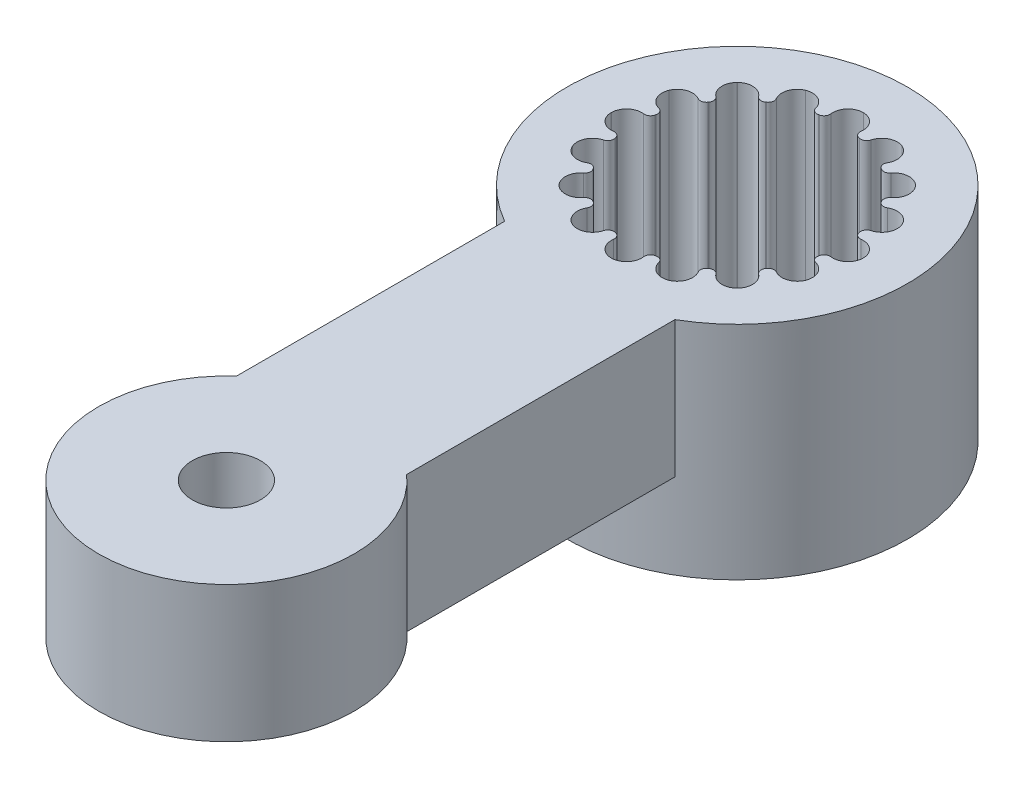
SolidWorks part; units mm, degrees
ref_plane "Ön Düzlem" through (0, 0, 0) normal (0, 0, 1) x (1, 0, 0)
ref_plane "Üst Düzlem" through (0, 0, 0) normal (0, 1, 0) x (1, 0, 0)
ref_plane "Sağ Düzlem" through (0, 0, 0) normal (1, 0, 0) x (0, 0, -1)
sketch "Sketch1" plane through (0, 0, 0) normal (0, 1, 0) x (1, 0, 0)
  circle A0 centre (0, 0) radius 6.1
  circle A1 centre (0, 0) radius 10
  dimension "D1" = 12.2
  dimension "D2" = 20
extrude "Boss-Extrude1" add sketch "Sketch1" along normal blind 8
sketch "Sketch2" plane through (0, 8, 0) normal (0, 1, 0) x (1, 0, 0)
  line L0 (0, 0) -> (0, 7.4) construction
  circle A0 centre (0, 0) radius 7.4 construction
  arc A1 (-0.0006, 7.4) -> (-0.887, 6.3783) centre (0.0047, 6.5) ccw
  circle A2 centre (0, 0) radius 6.1 construction
  arc A3 (0.0006, 7.4) -> (0.887, 6.3783) centre (-0.0047, 6.5) cw
  arc A4 (-0.0006, 7.4) -> (0.0006, 7.4) centre (0, 7.3) cw
  arc A5 (2.8324, 6.8365) -> (3.2603, 5.5533) centre (2.4831, 6.007) cw
  arc A6 (2.8313, 6.8369) -> (1.6214, 6.2322) centre (2.4918, 6.0034) ccw
  arc A7 (2.8313, 6.8369) -> (2.8324, 6.8365) centre (2.7936, 6.7443) cw
  arc A8 (5.233, 5.2322) -> (5.1373, 3.8829) centre (4.5929, 4.5996) cw
  arc A9 (5.2322, 5.233) -> (3.8829, 5.1373) centre (4.5996, 4.5929) ccw
  arc A10 (5.2322, 5.233) -> (5.233, 5.2322) centre (5.1619, 5.1619) cw
  arc A11 (6.8369, 2.8313) -> (6.2322, 1.6214) centre (6.0034, 2.4918) cw
  arc A12 (6.8365, 2.8324) -> (5.5533, 3.2603) centre (6.007, 2.4831) ccw
  arc A13 (6.8365, 2.8324) -> (6.8369, 2.8313) centre (6.7443, 2.7936) cw
  arc A14 (7.4, -0.0006) -> (6.3783, -0.887) centre (6.5, 0.0047) cw
  arc A15 (7.4, 0.0006) -> (6.3783, 0.887) centre (6.5, -0.0047) ccw
  arc A16 (7.4, 0.0006) -> (7.4, -0.0006) centre (7.3, 0) cw
  arc A17 (6.8365, -2.8324) -> (5.5533, -3.2603) centre (6.007, -2.4831) cw
  arc A18 (6.8369, -2.8313) -> (6.2322, -1.6214) centre (6.0034, -2.4918) ccw
  arc A19 (6.8369, -2.8313) -> (6.8365, -2.8324) centre (6.7443, -2.7936) cw
  arc A20 (5.2322, -5.233) -> (3.8829, -5.1373) centre (4.5996, -4.5928) cw
  arc A21 (5.233, -5.2322) -> (5.1373, -3.8829) centre (4.5929, -4.5996) ccw
  arc A22 (5.233, -5.2322) -> (5.2322, -5.233) centre (5.1619, -5.1619) cw
  arc A23 (2.8313, -6.8369) -> (1.6214, -6.2322) centre (2.4918, -6.0034) cw
  arc A24 (2.8324, -6.8365) -> (3.2603, -5.5533) centre (2.4831, -6.007) ccw
  arc A25 (2.8324, -6.8365) -> (2.8313, -6.8369) centre (2.7936, -6.7443) cw
  arc A26 (-0.0006, -7.4) -> (-0.887, -6.3783) centre (0.0048, -6.5) cw
  arc A27 (0.0006, -7.4) -> (0.887, -6.3783) centre (-0.0047, -6.5) ccw
  arc A28 (0.0006, -7.4) -> (-0.0006, -7.4) centre (0, -7.3) cw
  arc A29 (-2.8324, -6.8365) -> (-3.2603, -5.5533) centre (-2.4831, -6.007) cw
  arc A30 (-2.8313, -6.8369) -> (-1.6214, -6.2322) centre (-2.4918, -6.0034) ccw
  arc A31 (-2.8313, -6.8369) -> (-2.8324, -6.8365) centre (-2.7936, -6.7443) cw
  arc A32 (-5.233, -5.2322) -> (-5.1373, -3.8829) centre (-4.5928, -4.5996) cw
  arc A33 (-5.2322, -5.233) -> (-3.8829, -5.1373) centre (-4.5996, -4.5929) ccw
  arc A34 (-5.2322, -5.233) -> (-5.233, -5.2322) centre (-5.1619, -5.1619) cw
  arc A35 (-6.8369, -2.8313) -> (-6.2322, -1.6214) centre (-6.0034, -2.4918) cw
  arc A36 (-6.8365, -2.8324) -> (-5.5533, -3.2603) centre (-6.007, -2.4831) ccw
  arc A37 (-6.8365, -2.8324) -> (-6.8369, -2.8313) centre (-6.7443, -2.7936) cw
  arc A38 (-7.4, 0.0006) -> (-6.3783, 0.887) centre (-6.5, -0.0047) cw
  arc A39 (-7.4, -0.0006) -> (-6.3783, -0.887) centre (-6.5, 0.0047) ccw
  arc A40 (-7.4, -0.0006) -> (-7.4, 0.0006) centre (-7.3, 0) cw
  arc A41 (-6.8365, 2.8324) -> (-5.5533, 3.2603) centre (-6.007, 2.4831) cw
  arc A42 (-6.8369, 2.8313) -> (-6.2322, 1.6214) centre (-6.0034, 2.4918) ccw
  arc A43 (-6.8369, 2.8313) -> (-6.8365, 2.8324) centre (-6.7443, 2.7936) cw
  arc A44 (-5.2322, 5.233) -> (-3.8829, 5.1373) centre (-4.5996, 4.5928) cw
  arc A45 (-5.233, 5.2322) -> (-5.1373, 3.8829) centre (-4.5928, 4.5996) ccw
  arc A46 (-5.233, 5.2322) -> (-5.2322, 5.233) centre (-5.1619, 5.1619) cw
  arc A47 (-2.8313, 6.8369) -> (-1.6214, 6.2322) centre (-2.4918, 6.0034) cw
  arc A48 (-2.8324, 6.8365) -> (-3.2603, 5.5533) centre (-2.4831, 6.007) ccw
  arc A49 (-2.8324, 6.8365) -> (-2.8313, 6.8369) centre (-2.7936, 6.7443) cw
  arc A50 (-1.1668, 5.9874) -> (-1.2133, 5.9781) centre (0, 0) ccw
  arc A51 (-3.3693, 5.0851) -> (-3.4086, 5.0588) centre (0, 0) ccw
  arc A52 (-5.0588, 3.4086) -> (-5.0851, 3.3693) centre (0, 0) ccw
  arc A53 (-5.9781, 1.2133) -> (-5.9874, 1.1668) centre (0, 0) ccw
  arc A54 (-5.9874, -1.1668) -> (-5.9781, -1.2133) centre (0, 0) ccw
  arc A55 (-5.0851, -3.3693) -> (-5.0588, -3.4086) centre (0, 0) ccw
  arc A56 (-3.4086, -5.0588) -> (-3.3693, -5.0851) centre (0, 0) ccw
  arc A57 (-1.2133, -5.9781) -> (-1.1668, -5.9874) centre (0, 0) ccw
  arc A58 (1.1668, -5.9874) -> (1.2133, -5.9781) centre (0, 0) ccw
  arc A59 (3.3693, -5.0851) -> (3.4086, -5.0588) centre (0, 0) ccw
  arc A60 (5.0588, -3.4086) -> (5.0851, -3.3693) centre (0, 0) ccw
  arc A61 (5.9781, -1.2133) -> (5.9874, -1.1668) centre (0, 0) ccw
  arc A62 (5.9874, 1.1668) -> (5.9781, 1.2133) centre (0, 0) ccw
  arc A63 (5.0851, 3.3693) -> (5.0588, 3.4086) centre (0, 0) ccw
  arc A64 (3.4086, 5.0588) -> (3.3693, 5.0851) centre (0, 0) ccw
  arc A65 (1.2133, 5.9781) -> (1.1668, 5.9874) centre (0, 0) ccw
  arc A66 (-1.1668, 5.9874) -> (-0.887, 6.3783) centre (-1.2338, 6.3309) ccw
  arc A67 (-1.2133, 5.9781) -> (-1.6214, 6.2322) centre (-1.2829, 6.3211) cw
  arc A68 (-3.3693, 5.0851) -> (-3.2603, 5.5533) centre (-3.5626, 5.3768) ccw
  arc A69 (-3.4086, 5.0588) -> (-3.8829, 5.1373) centre (-3.6042, 5.349) cw
  arc A70 (-5.0851, 3.3693) -> (-5.5533, 3.2603) centre (-5.3769, 3.5626) cw
  arc A71 (-5.0588, 3.4086) -> (-5.1373, 3.8829) centre (-5.349, 3.6042) ccw
  arc A72 (-5.9781, 1.2133) -> (-6.2322, 1.6214) centre (-6.3211, 1.2829) ccw
  arc A73 (-5.9874, 1.1668) -> (-6.3783, 0.887) centre (-6.3309, 1.2338) cw
  arc A74 (-5.9874, -1.1668) -> (-6.3783, -0.887) centre (-6.3309, -1.2338) ccw
  arc A75 (-6.2322, -1.6214) -> (-5.9781, -1.2133) centre (-6.3211, -1.2829) ccw
  arc A76 (-5.0588, -3.4086) -> (-5.1373, -3.8829) centre (-5.349, -3.6042) cw
  arc A77 (-5.0851, -3.3693) -> (-5.5533, -3.2603) centre (-5.3768, -3.5626) ccw
  arc A78 (-3.4086, -5.0588) -> (-3.8829, -5.1373) centre (-3.6042, -5.349) ccw
  arc A79 (-3.2603, -5.5533) -> (-3.3693, -5.0851) centre (-3.5626, -5.3769) ccw
  arc A80 (-1.2133, -5.9781) -> (-1.6214, -6.2322) centre (-1.2829, -6.3211) ccw
  arc A81 (-0.887, -6.3783) -> (-1.1668, -5.9874) centre (-1.2338, -6.3309) ccw
  arc A82 (1.1668, -5.9874) -> (0.887, -6.3783) centre (1.2338, -6.3309) ccw
  arc A83 (1.2133, -5.9781) -> (1.6214, -6.2322) centre (1.2829, -6.3211) cw
  arc A84 (3.3693, -5.0851) -> (3.2603, -5.5533) centre (3.5626, -5.3768) ccw
  arc A85 (3.4086, -5.0588) -> (3.8829, -5.1373) centre (3.6042, -5.349) cw
  arc A86 (5.0588, -3.4086) -> (5.1373, -3.8829) centre (5.349, -3.6042) ccw
  arc A87 (5.0851, -3.3693) -> (5.5533, -3.2603) centre (5.3769, -3.5626) cw
  arc A88 (5.9781, -1.2133) -> (6.2322, -1.6214) centre (6.3211, -1.2829) ccw
  arc A89 (5.9874, -1.1668) -> (6.3783, -0.887) centre (6.3309, -1.2338) cw
  arc A90 (5.9874, 1.1668) -> (6.3783, 0.887) centre (6.3309, 1.2338) ccw
  arc A91 (5.9781, 1.2133) -> (6.2322, 1.6214) centre (6.3211, 1.2829) cw
  arc A92 (5.0851, 3.3693) -> (5.5533, 3.2603) centre (5.3768, 3.5626) ccw
  arc A93 (5.0588, 3.4086) -> (5.1373, 3.8829) centre (5.349, 3.6042) cw
  arc A94 (3.4086, 5.0588) -> (3.8829, 5.1373) centre (3.6042, 5.349) ccw
  arc A95 (3.3693, 5.0851) -> (3.2603, 5.5533) centre (3.5626, 5.3769) cw
  arc A96 (1.2133, 5.9781) -> (1.6214, 6.2322) centre (1.2829, 6.3211) ccw
  arc A97 (1.1668, 5.9874) -> (0.887, 6.3783) centre (1.2338, 6.3309) cw
  circle A98 centre (0, 0) radius 6.1
  point P15 (-0.775, 6.0506)
  point P121 (0, 0)
  point P132 (-4.8264, 3.7304)
  point P185 (0.775, 6.0506)
  circle M50 centre (0, 0) radius 6.1
  dimension "D1" = 14.8
  dimension "D3" = 0.9
  dimension "D4" = 0.1
  dimension "D6" = 0.35
  dimension "D2" = 1.55
  dimension "D5" = 16
extrude "Cut-Extrude1" cut sketch "Sketch2" against normal blind 8 contours A71 A69 A44 A46 A45 M50 | A68 A67 A47 A49 A48 M50
sketch "Sketch3" plane through (0, 8, 0) normal (0, 1, 0) x (1, 0, 0)
  line L0 (0, 0) -> (0, -30) construction
  line L1 (-5, -8.6603) -> (-5, -24.4098)
  line L2 (5, -8.6603) -> (5, -24.4098)
  arc A0 (-5, -24.4098) -> (5, -24.4098) centre (0, -30) ccw
  circle A1 centre (0, 0) radius 10 construction
  arc A2 (-5, -8.6603) -> (5, -8.6603) centre (0, 0) ccw
  circle A3 centre (0, -30) radius 2
  dimension "D2" = 15
  dimension "D4" = 4
  dimension "D5" = 10
  dimension "D1" = 30
  dimension "D3" = 5
extrude "Boss-Extrude2" add sketch "Sketch3" against normal blind 8
sketch "Sketch4" plane through (0, 0, 0) normal (0, -1, 0) x (1, 0, 0)
  line L1 (2.1073, 33.65) -> (-2.1073, 33.65)
  line L2 (-2.1073, 33.65) -> (-4.2147, 30)
  line L3 (-4.2147, 30) -> (-2.1073, 26.35)
  line L4 (-2.1073, 26.35) -> (2.1073, 26.35)
  line L5 (2.1073, 26.35) -> (4.2147, 30)
  line L6 (4.2147, 30) -> (2.1073, 33.65)
  circle A0 centre (0, 30) radius 3.65 construction
  dimension "D1" = 7.3
extrude "Cut-Extrude2" cut sketch "Sketch4" against normal blind 5
sketch "Çizim2" plane through (0, 0, 0) normal (0, -1, 0) x (1, 0, 0)
  circle A0 centre (0, 0) radius 10
  arc A1 (-5, 8.6603) -> (5, 8.6603) centre (0, 0) ccw construction
extrude "Yükseklik-Ekstrüzyon1" add sketch "Çizim2" along normal blind 5
sketch "Çizim3" plane through (0, 0, 0) normal (0, 1, 0) x (1, 0, 0)
  line L16 (-0.0006, -7.4) -> (0.0006, -7.4)
  line L17 (2.8313, -6.8369) -> (2.8324, -6.8365)
  line L18 (5.2322, -5.233) -> (5.233, -5.2322)
  line L19 (6.8365, -2.8324) -> (6.8369, -2.8313)
  line L20 (7.4, -0.0006) -> (7.4, 0.0006)
  line L21 (6.8369, 2.8313) -> (6.8365, 2.8324)
  line L22 (5.233, 5.2322) -> (5.2322, 5.233)
  line L23 (2.8324, 6.8365) -> (2.8313, 6.8369)
  line L24 (0.0006, 7.4) -> (-0.0006, 7.4)
  line L25 (-2.8313, 6.8369) -> (-2.8324, 6.8365)
  line L26 (-5.2322, 5.233) -> (-5.233, 5.2322)
  line L27 (-6.8365, 2.8324) -> (-6.8369, 2.8313)
  line L28 (-7.4, 0.0006) -> (-7.4, -0.0006)
  line L29 (-6.8369, -2.8313) -> (-6.8365, -2.8324)
  line L30 (-5.233, -5.2322) -> (-5.2322, -5.233)
  line L31 (-2.8324, -6.8365) -> (-2.8313, -6.8369)
  line L32 (-0.0006, -7.4) -> (0.0006, -7.4)
  line L33 (2.8313, -6.8369) -> (2.8324, -6.8365)
  line L34 (5.2322, -5.233) -> (5.233, -5.2322)
  line L35 (6.8365, -2.8324) -> (6.8369, -2.8313)
  line L36 (7.4, -0.0006) -> (7.4, 0.0006)
  line L37 (6.8369, 2.8313) -> (6.8365, 2.8324)
  line L38 (5.233, 5.2322) -> (5.2322, 5.233)
  line L39 (2.8324, 6.8365) -> (2.8313, 6.8369)
  line L40 (0.0006, 7.4) -> (-0.0006, 7.4)
  line L41 (-2.8313, 6.8369) -> (-2.8324, 6.8365)
  line L42 (-5.2322, 5.233) -> (-5.233, 5.2322)
  line L43 (-6.8365, 2.8324) -> (-6.8369, 2.8313)
  line L44 (-7.4, 0.0006) -> (-7.4, -0.0006)
  line L45 (-6.8369, -2.8313) -> (-6.8365, -2.8324)
  line L46 (-5.233, -5.2322) -> (-5.2322, -5.233)
  line L47 (-2.8324, -6.8365) -> (-2.8313, -6.8369)
  arc A80 (-1.2133, -5.9781) -> (-1.1668, -5.9874) centre (0, 0) ccw
  arc A81 (-0.887, -6.3783) -> (-1.1668, -5.9874) centre (-1.2338, -6.3309) ccw
  arc A82 (-0.887, -6.3783) -> (-0.0006, -7.4) centre (0.0048, -6.5) ccw
  arc A83 (0.0006, -7.4) -> (0.887, -6.3783) centre (-0.0047, -6.5) ccw
  arc A84 (1.1668, -5.9874) -> (0.887, -6.3783) centre (1.2338, -6.3309) ccw
  arc A85 (1.1668, -5.9874) -> (1.2133, -5.9781) centre (0, 0) ccw
  arc A86 (1.6214, -6.2322) -> (1.2133, -5.9781) centre (1.2829, -6.3211) ccw
  arc A87 (1.6214, -6.2322) -> (2.8313, -6.8369) centre (2.4918, -6.0034) ccw
  arc A88 (2.8324, -6.8365) -> (3.2603, -5.5533) centre (2.4831, -6.007) ccw
  arc A89 (3.3693, -5.0851) -> (3.2603, -5.5533) centre (3.5626, -5.3768) ccw
  arc A90 (3.3693, -5.0851) -> (3.4086, -5.0588) centre (0, 0) ccw
  arc A91 (3.8829, -5.1373) -> (3.4086, -5.0588) centre (3.6042, -5.349) ccw
  arc A92 (3.8829, -5.1373) -> (5.2322, -5.233) centre (4.5996, -4.5928) ccw
  arc A93 (5.233, -5.2322) -> (5.1373, -3.8829) centre (4.5929, -4.5996) ccw
  arc A94 (5.0588, -3.4086) -> (5.1373, -3.8829) centre (5.349, -3.6042) ccw
  arc A95 (5.0588, -3.4086) -> (5.0851, -3.3693) centre (0, 0) ccw
  arc A96 (5.5533, -3.2603) -> (5.0851, -3.3693) centre (5.3769, -3.5626) ccw
  arc A97 (5.5533, -3.2603) -> (6.8365, -2.8324) centre (6.007, -2.4831) ccw
  arc A98 (6.8369, -2.8313) -> (6.2322, -1.6214) centre (6.0034, -2.4918) ccw
  arc A99 (5.9781, -1.2133) -> (6.2322, -1.6214) centre (6.3211, -1.2829) ccw
  arc A100 (5.9781, -1.2133) -> (5.9874, -1.1668) centre (0, 0) ccw
  arc A101 (6.3783, -0.887) -> (5.9874, -1.1668) centre (6.3309, -1.2338) ccw
  arc A102 (6.3783, -0.887) -> (7.4, -0.0006) centre (6.5, 0.0047) ccw
  arc A103 (7.4, 0.0006) -> (6.3783, 0.887) centre (6.5, -0.0047) ccw
  arc A104 (5.9874, 1.1668) -> (6.3783, 0.887) centre (6.3309, 1.2338) ccw
  arc A105 (5.9874, 1.1668) -> (5.9781, 1.2133) centre (0, 0) ccw
  arc A106 (6.2322, 1.6214) -> (5.9781, 1.2133) centre (6.3211, 1.2829) ccw
  arc A107 (6.2322, 1.6214) -> (6.8369, 2.8313) centre (6.0034, 2.4918) ccw
  arc A108 (6.8365, 2.8324) -> (5.5533, 3.2603) centre (6.007, 2.4831) ccw
  arc A109 (5.0851, 3.3693) -> (5.5533, 3.2603) centre (5.3768, 3.5626) ccw
  arc A110 (5.0851, 3.3693) -> (5.0588, 3.4086) centre (0, 0) ccw
  arc A111 (5.1373, 3.8829) -> (5.0588, 3.4086) centre (5.349, 3.6042) ccw
  arc A112 (5.1373, 3.8829) -> (5.233, 5.2322) centre (4.5929, 4.5996) ccw
  arc A113 (5.2322, 5.233) -> (3.8829, 5.1373) centre (4.5996, 4.5929) ccw
  arc A114 (3.4086, 5.0588) -> (3.8829, 5.1373) centre (3.6042, 5.349) ccw
  arc A115 (3.4086, 5.0588) -> (3.3693, 5.0851) centre (0, 0) ccw
  arc A116 (3.2603, 5.5533) -> (3.3693, 5.0851) centre (3.5626, 5.3769) ccw
  arc A117 (3.2603, 5.5533) -> (2.8324, 6.8365) centre (2.4831, 6.007) ccw
  arc A118 (2.8313, 6.8369) -> (1.6214, 6.2322) centre (2.4918, 6.0034) ccw
  arc A119 (1.2133, 5.9781) -> (1.6214, 6.2322) centre (1.2829, 6.3211) ccw
  arc A120 (1.2133, 5.9781) -> (1.1668, 5.9874) centre (0, 0) ccw
  arc A121 (0.887, 6.3783) -> (1.1668, 5.9874) centre (1.2338, 6.3309) ccw
  arc A122 (0.887, 6.3783) -> (0.0006, 7.4) centre (-0.0047, 6.5) ccw
  arc A123 (-0.0006, 7.4) -> (-0.887, 6.3783) centre (0.0047, 6.5) ccw
  arc A124 (-1.1668, 5.9874) -> (-0.887, 6.3783) centre (-1.2338, 6.3309) ccw
  arc A125 (-1.1668, 5.9874) -> (-1.2133, 5.9781) centre (0, 0) ccw
  arc A126 (-1.6214, 6.2322) -> (-1.2133, 5.9781) centre (-1.2829, 6.3211) ccw
  arc A127 (-1.6214, 6.2322) -> (-2.8313, 6.8369) centre (-2.4918, 6.0034) ccw
  arc A128 (-2.8324, 6.8365) -> (-3.2603, 5.5533) centre (-2.4831, 6.007) ccw
  arc A129 (-3.3693, 5.0851) -> (-3.2603, 5.5533) centre (-3.5626, 5.3768) ccw
  arc A130 (-3.3693, 5.0851) -> (-3.4086, 5.0588) centre (0, 0) ccw
  arc A131 (-3.8829, 5.1373) -> (-3.4086, 5.0588) centre (-3.6042, 5.349) ccw
  arc A132 (-3.8829, 5.1373) -> (-5.2322, 5.233) centre (-4.5996, 4.5928) ccw
  arc A133 (-5.233, 5.2322) -> (-5.1373, 3.8829) centre (-4.5928, 4.5996) ccw
  arc A134 (-5.0588, 3.4086) -> (-5.1373, 3.8829) centre (-5.349, 3.6042) ccw
  arc A135 (-5.0588, 3.4086) -> (-5.0851, 3.3693) centre (0, 0) ccw
  arc A136 (-5.5533, 3.2603) -> (-5.0851, 3.3693) centre (-5.3769, 3.5626) ccw
  arc A137 (-5.5533, 3.2603) -> (-6.8365, 2.8324) centre (-6.007, 2.4831) ccw
  arc A138 (-6.8369, 2.8313) -> (-6.2322, 1.6214) centre (-6.0034, 2.4918) ccw
  arc A139 (-5.9781, 1.2133) -> (-6.2322, 1.6214) centre (-6.3211, 1.2829) ccw
  arc A140 (-5.9781, 1.2133) -> (-5.9874, 1.1668) centre (0, 0) ccw
  arc A141 (-6.3783, 0.887) -> (-5.9874, 1.1668) centre (-6.3309, 1.2338) ccw
  arc A142 (-6.3783, 0.887) -> (-7.4, 0.0006) centre (-6.5, -0.0047) ccw
  arc A143 (-7.4, -0.0006) -> (-6.3783, -0.887) centre (-6.5, 0.0047) ccw
  arc A144 (-5.9874, -1.1668) -> (-6.3783, -0.887) centre (-6.3309, -1.2338) ccw
  arc A145 (-5.9874, -1.1668) -> (-5.9781, -1.2133) centre (0, 0) ccw
  arc A146 (-6.2322, -1.6214) -> (-5.9781, -1.2133) centre (-6.3211, -1.2829) ccw
  arc A147 (-6.2322, -1.6214) -> (-6.8369, -2.8313) centre (-6.0034, -2.4918) ccw
  arc A148 (-6.8365, -2.8324) -> (-5.5533, -3.2603) centre (-6.007, -2.4831) ccw
  arc A149 (-5.0851, -3.3693) -> (-5.5533, -3.2603) centre (-5.3768, -3.5626) ccw
  arc A150 (-5.0851, -3.3693) -> (-5.0588, -3.4086) centre (0, 0) ccw
  arc A151 (-5.1373, -3.8829) -> (-5.0588, -3.4086) centre (-5.349, -3.6042) ccw
  arc A152 (-5.1373, -3.8829) -> (-5.233, -5.2322) centre (-4.5928, -4.5996) ccw
  arc A153 (-5.2322, -5.233) -> (-3.8829, -5.1373) centre (-4.5996, -4.5929) ccw
  arc A154 (-3.4086, -5.0588) -> (-3.8829, -5.1373) centre (-3.6042, -5.349) ccw
  arc A155 (-3.4086, -5.0588) -> (-3.3693, -5.0851) centre (0, 0) ccw
  arc A156 (-3.2603, -5.5533) -> (-3.3693, -5.0851) centre (-3.5626, -5.3769) ccw
  arc A157 (-3.2603, -5.5533) -> (-2.8324, -6.8365) centre (-2.4831, -6.007) ccw
  arc A158 (-2.8313, -6.8369) -> (-1.6214, -6.2322) centre (-2.4918, -6.0034) ccw
  arc A159 (-1.2133, -5.9781) -> (-1.6214, -6.2322) centre (-1.2829, -6.3211) ccw
  arc A160 (-1.2133, -5.9781) -> (-1.1668, -5.9874) centre (0, 0) ccw
  arc A161 (-0.887, -6.3783) -> (-1.1668, -5.9874) centre (-1.2338, -6.3309) ccw
  arc A162 (-0.887, -6.3783) -> (-0.0006, -7.4) centre (0.0048, -6.5) ccw
  arc A163 (0.0006, -7.4) -> (0.887, -6.3783) centre (-0.0047, -6.5) ccw
  arc A164 (1.1668, -5.9874) -> (0.887, -6.3783) centre (1.2338, -6.3309) ccw
  arc A165 (1.1668, -5.9874) -> (1.2133, -5.9781) centre (0, 0) ccw
  arc A166 (1.6214, -6.2322) -> (1.2133, -5.9781) centre (1.2829, -6.3211) ccw
  arc A167 (1.6214, -6.2322) -> (2.8313, -6.8369) centre (2.4918, -6.0034) ccw
  arc A168 (2.8324, -6.8365) -> (3.2603, -5.5533) centre (2.4831, -6.007) ccw
  arc A169 (3.3693, -5.0851) -> (3.2603, -5.5533) centre (3.5626, -5.3768) ccw
  arc A170 (3.3693, -5.0851) -> (3.4086, -5.0588) centre (0, 0) ccw
  arc A171 (3.8829, -5.1373) -> (3.4086, -5.0588) centre (3.6042, -5.349) ccw
  arc A172 (3.8829, -5.1373) -> (5.2322, -5.233) centre (4.5996, -4.5928) ccw
  arc A173 (5.233, -5.2322) -> (5.1373, -3.8829) centre (4.5929, -4.5996) ccw
  arc A174 (5.0588, -3.4086) -> (5.1373, -3.8829) centre (5.349, -3.6042) ccw
  arc A175 (5.0588, -3.4086) -> (5.0851, -3.3693) centre (0, 0) ccw
  arc A176 (5.5533, -3.2603) -> (5.0851, -3.3693) centre (5.3769, -3.5626) ccw
  arc A177 (5.5533, -3.2603) -> (6.8365, -2.8324) centre (6.007, -2.4831) ccw
  arc A178 (6.8369, -2.8313) -> (6.2322, -1.6214) centre (6.0034, -2.4918) ccw
  arc A179 (5.9781, -1.2133) -> (6.2322, -1.6214) centre (6.3211, -1.2829) ccw
  arc A180 (5.9781, -1.2133) -> (5.9874, -1.1668) centre (0, 0) ccw
  arc A181 (6.3783, -0.887) -> (5.9874, -1.1668) centre (6.3309, -1.2338) ccw
  arc A182 (6.3783, -0.887) -> (7.4, -0.0006) centre (6.5, 0.0047) ccw
  arc A183 (7.4, 0.0006) -> (6.3783, 0.887) centre (6.5, -0.0047) ccw
  arc A184 (5.9874, 1.1668) -> (6.3783, 0.887) centre (6.3309, 1.2338) ccw
  arc A185 (5.9874, 1.1668) -> (5.9781, 1.2133) centre (0, 0) ccw
  arc A186 (6.2322, 1.6214) -> (5.9781, 1.2133) centre (6.3211, 1.2829) ccw
  arc A187 (6.2322, 1.6214) -> (6.8369, 2.8313) centre (6.0034, 2.4918) ccw
  arc A188 (6.8365, 2.8324) -> (5.5533, 3.2603) centre (6.007, 2.4831) ccw
  arc A189 (5.0851, 3.3693) -> (5.5533, 3.2603) centre (5.3768, 3.5626) ccw
  arc A190 (5.0851, 3.3693) -> (5.0588, 3.4086) centre (0, 0) ccw
  arc A191 (5.1373, 3.8829) -> (5.0588, 3.4086) centre (5.349, 3.6042) ccw
  arc A192 (5.1373, 3.8829) -> (5.233, 5.2322) centre (4.5929, 4.5996) ccw
  arc A193 (5.2322, 5.233) -> (3.8829, 5.1373) centre (4.5996, 4.5929) ccw
  arc A194 (3.4086, 5.0588) -> (3.8829, 5.1373) centre (3.6042, 5.349) ccw
  arc A195 (3.4086, 5.0588) -> (3.3693, 5.0851) centre (0, 0) ccw
  arc A196 (3.2603, 5.5533) -> (3.3693, 5.0851) centre (3.5626, 5.3769) ccw
  arc A197 (3.2603, 5.5533) -> (2.8324, 6.8365) centre (2.4831, 6.007) ccw
  arc A198 (2.8313, 6.8369) -> (1.6214, 6.2322) centre (2.4918, 6.0034) ccw
  arc A199 (1.2133, 5.9781) -> (1.6214, 6.2322) centre (1.2829, 6.3211) ccw
  arc A200 (1.2133, 5.9781) -> (1.1668, 5.9874) centre (0, 0) ccw
  arc A201 (0.887, 6.3783) -> (1.1668, 5.9874) centre (1.2338, 6.3309) ccw
  arc A202 (0.887, 6.3783) -> (0.0006, 7.4) centre (-0.0047, 6.5) ccw
  arc A203 (-0.0006, 7.4) -> (-0.887, 6.3783) centre (0.0047, 6.5) ccw
  arc A204 (-1.1668, 5.9874) -> (-0.887, 6.3783) centre (-1.2338, 6.3309) ccw
  arc A205 (-1.1668, 5.9874) -> (-1.2133, 5.9781) centre (0, 0) ccw
  arc A206 (-1.6214, 6.2322) -> (-1.2133, 5.9781) centre (-1.2829, 6.3211) ccw
  arc A207 (-1.6214, 6.2322) -> (-2.8313, 6.8369) centre (-2.4918, 6.0034) ccw
  arc A208 (-2.8324, 6.8365) -> (-3.2603, 5.5533) centre (-2.4831, 6.007) ccw
  arc A209 (-3.3693, 5.0851) -> (-3.2603, 5.5533) centre (-3.5626, 5.3768) ccw
  arc A210 (-3.3693, 5.0851) -> (-3.4086, 5.0588) centre (0, 0) ccw
  arc A211 (-3.8829, 5.1373) -> (-3.4086, 5.0588) centre (-3.6042, 5.349) ccw
  arc A212 (-3.8829, 5.1373) -> (-5.2322, 5.233) centre (-4.5996, 4.5928) ccw
  arc A213 (-5.233, 5.2322) -> (-5.1373, 3.8829) centre (-4.5928, 4.5996) ccw
  arc A214 (-5.0588, 3.4086) -> (-5.1373, 3.8829) centre (-5.349, 3.6042) ccw
  arc A215 (-5.0588, 3.4086) -> (-5.0851, 3.3693) centre (0, 0) ccw
  arc A216 (-5.5533, 3.2603) -> (-5.0851, 3.3693) centre (-5.3769, 3.5626) ccw
  arc A217 (-5.5533, 3.2603) -> (-6.8365, 2.8324) centre (-6.007, 2.4831) ccw
  arc A218 (-6.8369, 2.8313) -> (-6.2322, 1.6214) centre (-6.0034, 2.4918) ccw
  arc A219 (-5.9781, 1.2133) -> (-6.2322, 1.6214) centre (-6.3211, 1.2829) ccw
  arc A220 (-5.9781, 1.2133) -> (-5.9874, 1.1668) centre (0, 0) ccw
  arc A221 (-6.3783, 0.887) -> (-5.9874, 1.1668) centre (-6.3309, 1.2338) ccw
  arc A222 (-6.3783, 0.887) -> (-7.4, 0.0006) centre (-6.5, -0.0047) ccw
  arc A223 (-7.4, -0.0006) -> (-6.3783, -0.887) centre (-6.5, 0.0047) ccw
  arc A224 (-5.9874, -1.1668) -> (-6.3783, -0.887) centre (-6.3309, -1.2338) ccw
  arc A225 (-5.9874, -1.1668) -> (-5.9781, -1.2133) centre (0, 0) ccw
  arc A226 (-6.2322, -1.6214) -> (-5.9781, -1.2133) centre (-6.3211, -1.2829) ccw
  arc A227 (-6.2322, -1.6214) -> (-6.8369, -2.8313) centre (-6.0034, -2.4918) ccw
  arc A228 (-6.8365, -2.8324) -> (-5.5533, -3.2603) centre (-6.007, -2.4831) ccw
  arc A229 (-5.0851, -3.3693) -> (-5.5533, -3.2603) centre (-5.3768, -3.5626) ccw
  arc A230 (-5.0851, -3.3693) -> (-5.0588, -3.4086) centre (0, 0) ccw
  arc A231 (-5.1373, -3.8829) -> (-5.0588, -3.4086) centre (-5.349, -3.6042) ccw
  arc A232 (-5.1373, -3.8829) -> (-5.233, -5.2322) centre (-4.5928, -4.5996) ccw
  arc A233 (-5.2322, -5.233) -> (-3.8829, -5.1373) centre (-4.5996, -4.5929) ccw
  arc A234 (-3.4086, -5.0588) -> (-3.8829, -5.1373) centre (-3.6042, -5.349) ccw
  arc A235 (-3.4086, -5.0588) -> (-3.3693, -5.0851) centre (0, 0) ccw
  arc A236 (-3.2603, -5.5533) -> (-3.3693, -5.0851) centre (-3.5626, -5.3769) ccw
  arc A237 (-3.2603, -5.5533) -> (-2.8324, -6.8365) centre (-2.4831, -6.007) ccw
  arc A238 (-2.8313, -6.8369) -> (-1.6214, -6.2322) centre (-2.4918, -6.0034) ccw
  arc A239 (-1.2133, -5.9781) -> (-1.6214, -6.2322) centre (-1.2829, -6.3211) ccw
  dimension "D1" = 0
extrude "Kes-Ekstrüzyon1" cut sketch "Çizim3" against normal blind 10
